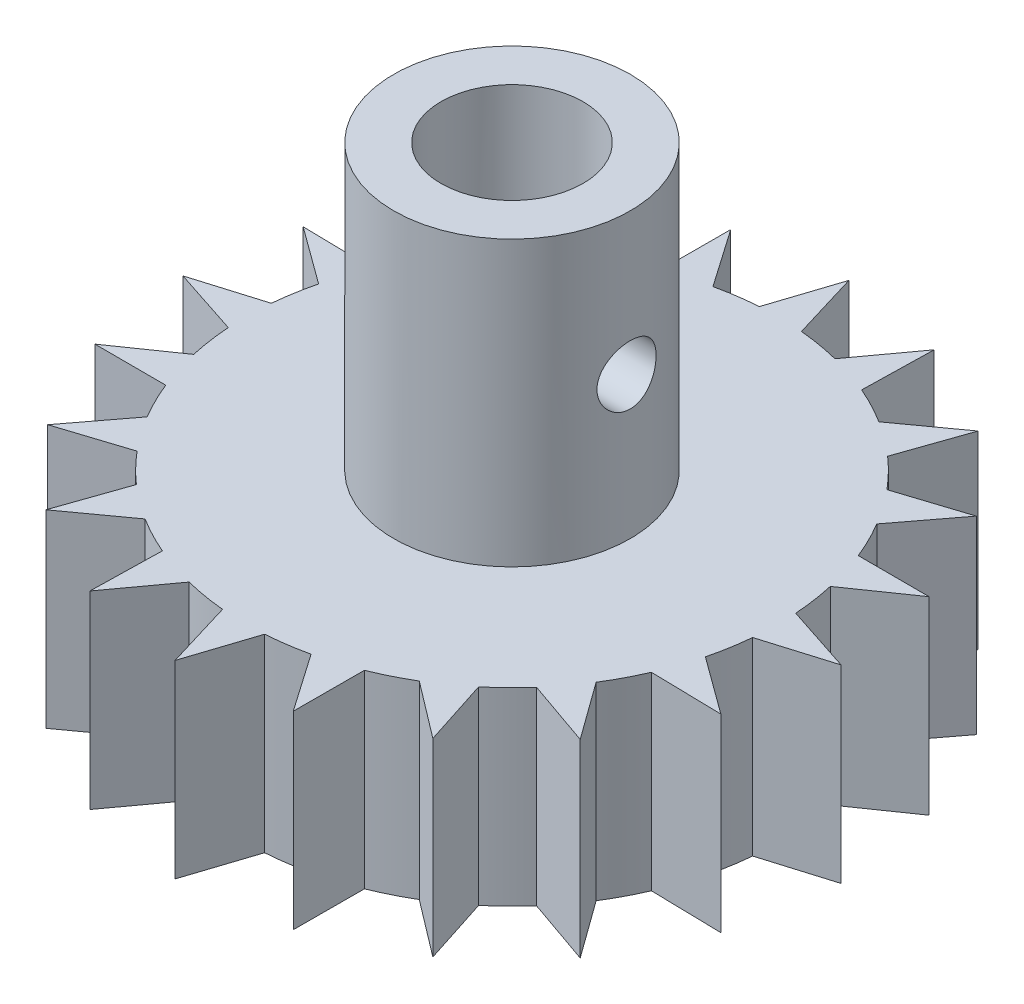
SolidWorks part; units mm, degrees
material "ABS"
ref_plane "Front Plane" through (0, 0, 0) normal (0, 0, 1) x (1, 0, 0)
ref_plane "Top Plane" through (0, 0, 0) normal (0, 1, 0) x (1, 0, 0)
ref_plane "Right Plane" through (0, 0, 0) normal (1, 0, 0) x (0, 0, -1)
sketch "Sketch2" plane through (0, 0, 0) normal (0, 1, 0) x (1, 0, 0)
  circle A0 centre (0, 0) radius 3
  circle A1 centre (0, 0) radius 5
  dimension "D1" = 6
  dimension "D2" = 10
extrude "Boss-Extrude1" add sketch "Sketch2" along normal blind 20
sketch "Sketch3" plane through (0, 0, 0) normal (1, 0, 0) x (0, 0, -1)
  circle A0 centre (0, 14) radius 1.25
  dimension "D1" = 2.5
  dimension "D2" = 14
extrude "Cut-Extrude1" cut sketch "Sketch3" against normal through all both and the other way through all
sketch "Sketch4" plane through (0, 0, 0) normal (0, -1, 0) x (1, 0, 0)
  line L0 (0, 0) -> (12.5325, 0) construction
  line L1 (11.2237, -0.7681) -> (14.0748, 0.1655)
  line L2 (14.0748, 0.1655) -> (11.2026, 1.0318)
  line L4 (13.437, -4.192) -> (10.9731, -2.4805)
  line L5 (10.4371, -4.1988) -> (13.437, -4.192)
  line L6 (11.484, -8.1391) -> (9.6695, -5.75)
  line L7 (8.6287, -7.2186) -> (11.484, -8.1391)
  line L8 (8.4068, -11.2895) -> (7.4194, -8.4566)
  line L9 (5.9757, -9.5317) -> (8.4068, -11.2895)
  line L10 (4.5067, -13.3348) -> (4.4431, -10.3355)
  line L11 (2.7378, -10.9118) -> (4.5067, -13.3348)
  line L12 (0.1655, -14.0748) -> (1.0318, -11.2026)
  line L13 (-0.7681, -11.2237) -> (0.1655, -14.0748)
  line L14 (-4.192, -13.437) -> (-2.4805, -10.9731)
  line L15 (-4.1988, -10.4371) -> (-4.192, -13.437)
  line L16 (-8.1391, -11.484) -> (-5.75, -9.6695)
  line L17 (-7.2186, -8.6287) -> (-8.1391, -11.484)
  line L18 (-11.2895, -8.4068) -> (-8.4566, -7.4194)
  line L19 (-9.5317, -5.9757) -> (-11.2895, -8.4068)
  line L20 (-13.3348, -4.5067) -> (-10.3355, -4.4431)
  line L21 (-10.9118, -2.7378) -> (-13.3348, -4.5067)
  line L22 (-14.0748, -0.1655) -> (-11.2026, -1.0318)
  line L23 (-11.2237, 0.7681) -> (-14.0748, -0.1655)
  line L24 (-13.437, 4.192) -> (-10.9731, 2.4805)
  line L25 (-10.4371, 4.1988) -> (-13.437, 4.192)
  line L26 (-11.484, 8.1391) -> (-9.6695, 5.75)
  line L27 (-8.6287, 7.2186) -> (-11.484, 8.1391)
  line L28 (-8.4068, 11.2895) -> (-7.4194, 8.4566)
  line L29 (-5.9757, 9.5317) -> (-8.4068, 11.2895)
  line L30 (-4.5067, 13.3348) -> (-4.4431, 10.3355)
  line L31 (-2.7378, 10.9118) -> (-4.5067, 13.3348)
  line L32 (-0.1655, 14.0748) -> (-1.0318, 11.2026)
  line L33 (0.7681, 11.2237) -> (-0.1655, 14.0748)
  line L34 (4.192, 13.437) -> (2.4805, 10.9731)
  line L35 (4.1988, 10.4371) -> (4.192, 13.437)
  line L36 (8.1391, 11.484) -> (5.75, 9.6695)
  line L37 (7.2186, 8.6287) -> (8.1391, 11.484)
  line L38 (11.2895, 8.4068) -> (8.4566, 7.4194)
  line L39 (9.5317, 5.9757) -> (11.2895, 8.4068)
  line L40 (13.3348, 4.5067) -> (10.3355, 4.4431)
  line L41 (10.9118, 2.7378) -> (13.3348, 4.5067)
  arc A0 (10.3355, 4.4431) -> (9.5317, 5.9757) centre (0, 0) ccw
  arc A1 (11.2026, 1.0318) -> (10.9118, 2.7378) centre (0, 0) ccw
  arc A2 (10.9731, -2.4805) -> (11.2237, -0.7681) centre (0, 0) ccw
  arc A3 (9.6695, -5.75) -> (10.4371, -4.1988) centre (0, 0) ccw
  arc A4 (7.4194, -8.4566) -> (8.6287, -7.2186) centre (0, 0) ccw
  arc A5 (4.4431, -10.3355) -> (5.9757, -9.5317) centre (0, 0) ccw
  arc A6 (1.0318, -11.2026) -> (2.7378, -10.9118) centre (0, 0) ccw
  arc A7 (-2.4805, -10.9731) -> (-0.7681, -11.2237) centre (0, 0) ccw
  arc A8 (-5.75, -9.6695) -> (-4.1988, -10.4371) centre (0, 0) ccw
  arc A9 (-8.4566, -7.4194) -> (-7.2186, -8.6287) centre (0, 0) ccw
  arc A10 (-10.3355, -4.4431) -> (-9.5317, -5.9757) centre (0, 0) ccw
  arc A11 (-11.2026, -1.0318) -> (-10.9118, -2.7378) centre (0, 0) ccw
  arc A12 (-10.9731, 2.4805) -> (-11.2237, 0.7681) centre (0, 0) ccw
  arc A13 (-9.6695, 5.75) -> (-10.4371, 4.1988) centre (0, 0) ccw
  arc A14 (-7.4194, 8.4566) -> (-8.6287, 7.2186) centre (0, 0) ccw
  arc A15 (-4.4431, 10.3355) -> (-5.9757, 9.5317) centre (0, 0) ccw
  arc A16 (-1.0318, 11.2026) -> (-2.7378, 10.9118) centre (0, 0) ccw
  arc A17 (2.4805, 10.9731) -> (0.7681, 11.2237) centre (0, 0) ccw
  arc A18 (5.75, 9.6695) -> (4.1988, 10.4371) centre (0, 0) ccw
  arc A19 (8.4566, 7.4194) -> (7.2186, 8.6287) centre (0, 0) ccw
  point P8 (0, 0)
  point P68 (0, 0)
  dimension "D2" = 22.5
  dimension "D1" = 3
  dimension "D4" = 1.8
  dimension "D3" = 20
extrude "Boss-Extrude2" add sketch "Sketch4" against normal blind 8
